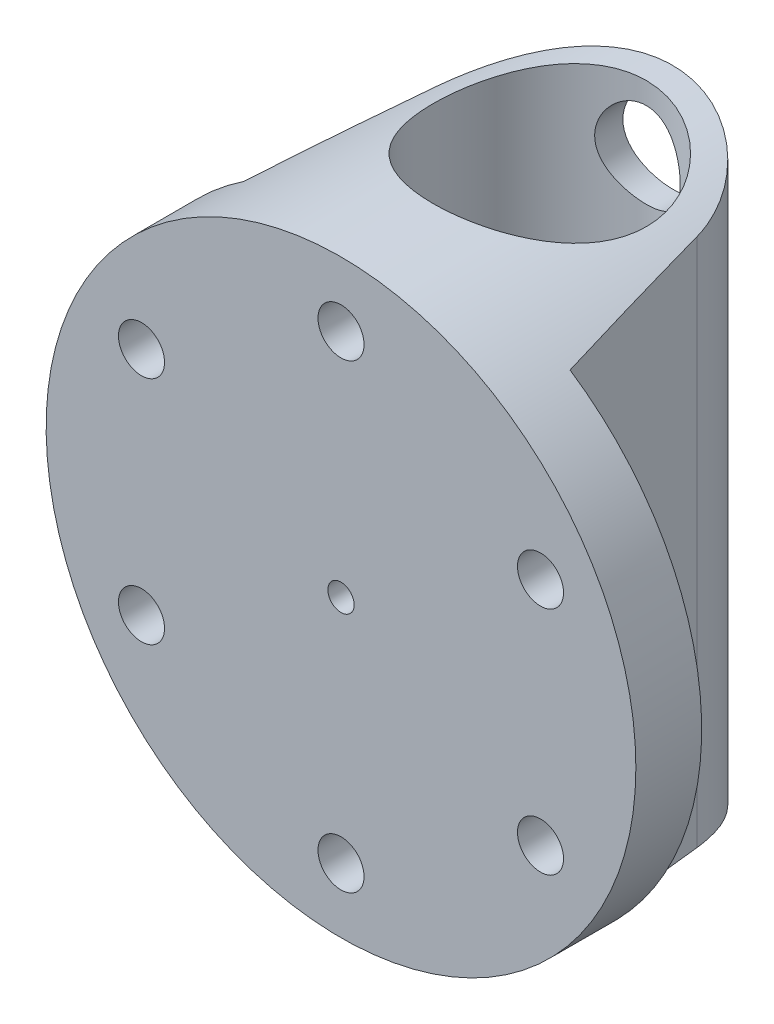
SolidWorks part; units mm, degrees
ref_plane "Front Plane" through (0, 0, 0) normal (0, 0, 1) x (1, 0, 0)
ref_plane "Top Plane" through (0, 0, 0) normal (0, 1, 0) x (1, 0, 0)
ref_plane "Right Plane" through (0, 0, 0) normal (1, 0, 0) x (0, 0, -1)
sketch "Sketch1" plane through (0, 0, 0) normal (0, 0, 1) x (1, 0, 0)
  circle A0 centre (0, 0) radius 22.4
  dimension "D1" = 44.8
extrude "Boss-Extrude1" add sketch "Sketch1" along normal blind 5
sketch "Sketch3" plane through (0, 0, 0) normal (0, 1, 0) x (1, 0, 0)
  line L0 (22.4, 0) -> (-22.4, 0) construction
  line L1 (0, -2.75) -> (0, 2.75) construction
  line L2 (-9.8911, 12.1435) -> (-12.4, 0)
  line L3 (22.4, 0) -> (-22.4, 0) construction
  line L4 (9.8911, 12.1435) -> (12.4, 0)
  line L5 (-12.4, 0) -> (12.4, 0)
  circle A0 centre (0, 10.1) radius 8.1
  arc A1 (9.8911, 12.1435) -> (-9.8911, 12.1435) centre (0, 10.1) ccw
  circle A2 centre (0, 10.1) radius 10.1 construction
  dimension "D2" = 16.2
  dimension "D3" = 10
  dimension "D4" = 10
  dimension "D1" = 2
extrude "Boss-Extrude2" add sketch "Sketch3" along normal up to surface and the other way blind 18 separate body up to face at (22.4, 0, 5)
sketch "Sketch4" plane through (0, 0, 0) normal (0, 0, -1) x (-1, 0, 0)
  line L0 (9.8911, -18) -> (12.4, -18) construction
  line L1 (-9.8911, -18) -> (9.8911, -18) construction
  line L2 (-12.4, -18) -> (-9.8911, -18) construction
  line L3 (9.8911, -18) -> (12.4, -18)
  line L4 (-9.8911, -18) -> (9.8911, -18)
  line L5 (-12.4, -18) -> (-9.8911, -18)
  line L6 (-12.4, -18) -> (-12.4, -18.6548)
  line L7 (12.4, -18) -> (12.4, -18.6548)
  circle A0 centre (0, 0) radius 22.4 construction
  arc A1 (-12.4, -18.6548) -> (12.4, -18.6548) centre (0, 0) ccw
extrude "Boss-Extrude5" add sketch "Sketch4" along normal blind 21
sketch "Sketch6" plane through (0, -18, 0) normal (0, 1, 0) x (1, 0, 0)
  line L5 (9.8911, 12.1435) -> (12.4, 0)
  line L6 (12.4, 0) -> (12.4, 21)
  line L7 (12.4, 21) -> (-12.4, 21)
  line L8 (-12.4, 21) -> (-12.4, 0)
  line L9 (-12.4, 0) -> (-9.8911, 12.1435)
  line L10 (9.8911, 12.1435) -> (12.4, 0)
  line L11 (12.4, 0) -> (12.4, 21)
  line L12 (12.4, 21) -> (-12.4, 21)
  line L13 (-12.4, 21) -> (-12.4, 0)
  line L14 (-12.4, 0) -> (-9.8911, 12.1435)
  arc A1 (9.8911, 12.1435) -> (-9.8911, 12.1435) centre (0, 10.1) ccw
  arc A2 (9.8911, 12.1435) -> (-9.8911, 12.1435) centre (0, 10.1) ccw
  dimension "D1" = 0
extrude "Cut-Extrude2" cut sketch "Sketch6" against normal blind 21
sketch "Sketch2" plane through (0, 0, 5) normal (0, 0, 1) x (1, 0, 0)
  line L0 (0, 0) -> (0, 22.4) construction
  line L1 (0, 0) -> (0, 17.5) construction
  circle A0 centre (0, 0) radius 17.5
  circle A1 centre (0, 17.5) radius 1.75
  circle A2 centre (0, 0) radius 22.4 construction
  circle A3 centre (15.1554, 8.75) radius 1.75
  circle A4 centre (15.1554, -8.75) radius 1.75
  circle A5 centre (0, -17.5) radius 1.75
  circle A6 centre (-15.1554, -8.75) radius 1.75
  circle A7 centre (-15.1554, 8.75) radius 1.75
  point P9 (0, 0)
  point P10 (8.75, -15.1554)
  point P20 (0, 0)
  dimension "D1" = 35
  dimension "D2" = 3.5
  dimension "D3" = 0
  dimension "D4" = 6
extrude "Cut-Extrude1" cut sketch "Sketch2" against normal through all contours A1 | A7 | A4 | A5 | A3 | A6
sketch "Sketch7" plane through (0, 0, 0) normal (0, 0, -1) x (-1, 0, 0)
  circle A0 centre (0, -17.5) radius 1.75 construction
  circle A1 centre (0, 17.5) radius 1.75 construction
  circle A2 centre (0, -17.5) radius 1.75
  circle A3 centre (0, 17.5) radius 1.75
  circle A4 centre (0, 17.5) radius 3.25
  circle A5 centre (0, -17.5) radius 3.25
  dimension "D1" = 1.5
extrude "Cut-Extrude3" cut sketch "Sketch7" against normal blind 1.5 and the other way blind 21
sketch "Sketch8" plane through (0, 0, 5) normal (0, 0, 1) x (1, 0, 0)
  circle A0 centre (0, 0) radius 1
  dimension "D1" = 2
extrude "Cut-Extrude4" cut sketch "Sketch8" against normal through all
